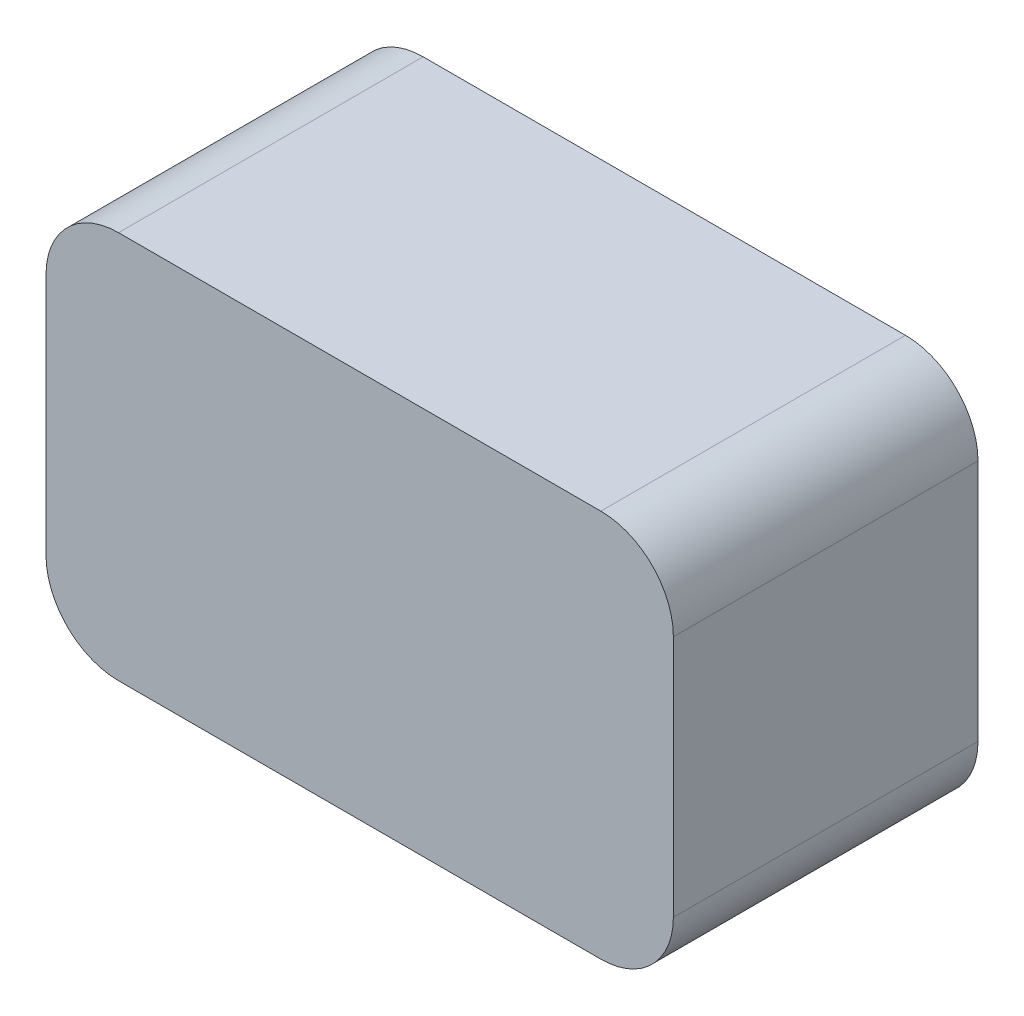
SolidWorks part; units mm, degrees
ref_plane "Płaszczyzna przednia" through (0, 0, 0) normal (0, 0, 1) x (1, 0, 0)
ref_plane "Płaszczyzna górna" through (0, 0, 0) normal (0, 1, 0) x (1, 0, 0)
ref_plane "Płaszczyzna prawa" through (0, 0, 0) normal (1, 0, 0) x (0, 0, -1)
sketch "Szkic1" plane through (0, 0, 0) normal (0, 0, 1) x (1, 0, 0)
  line L1 (-42.2351, 15.4291) -> (24.2649, 15.4291)
  line L2 (-52.2351, 5.4291) -> (-52.2351, -28.0709)
  line L3 (-42.2351, -38.0709) -> (24.2649, -38.0709)
  line L4 (34.2649, 5.4291) -> (34.2649, -28.0709)
  arc A0 (24.2649, 15.4291) -> (34.2649, 5.4291) centre (24.2649, 5.4291) cw
  arc A1 (24.2649, -38.0709) -> (34.2649, -28.0709) centre (24.2649, -28.0709) ccw
  arc A2 (-52.2351, -28.0709) -> (-42.2351, -38.0709) centre (-42.2351, -28.0709) ccw
  arc A3 (-42.2351, 15.4291) -> (-52.2351, 5.4291) centre (-42.2351, 5.4291) ccw
  point P6 (34.2649, 15.4291)
  point P11 (-52.2351, -38.0709)
  point P14 (-52.2351, 15.4291)
  dimension "D3" = 10
  dimension "D4" = 10
  dimension "D1" = 86.5
  dimension "D2" = 53.5
extrude "Dodanie-wyciągnięcie1" add sketch "Szkic1" along normal blind 42
ref_plane "Płaszczyzna symetrii" through (-8.9851, 0, 0) normal (-1, 0, 0) x (0, 0, 1)
